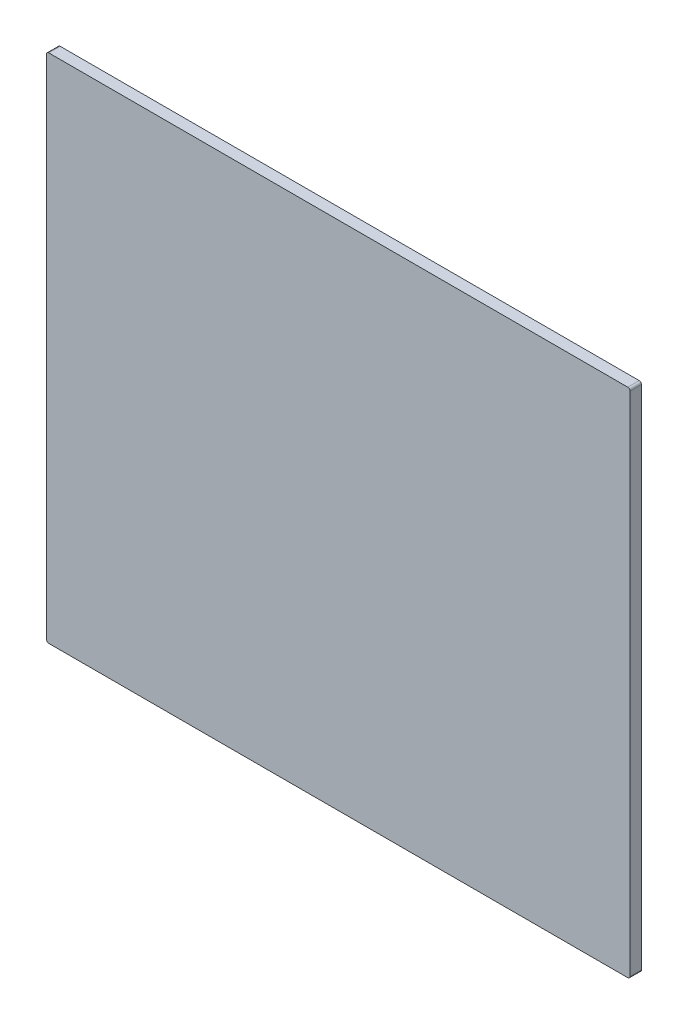
SolidWorks part; units mm, degrees
ref_plane "Front Plane" through (0, 0, 0) normal (0, 0, 1) x (1, 0, 0)
ref_plane "Top Plane" through (0, 0, 0) normal (0, 1, 0) x (1, 0, 0)
ref_plane "Right Plane" through (0, 0, 0) normal (1, 0, 0) x (0, 0, -1)
sketch "Sketch1" plane through (0, 0, 0) normal (0, 0, 1) x (1, 0, 0)
  line L1 (-224.9767, 260.7264) -> (422.7233, 260.7264)
  line L2 (-224.9767, 260.7264) -> (-224.9767, -306.9636)
  line L3 (-224.9767, -306.9636) -> (422.7233, -306.9636)
  line L4 (422.7233, 260.7264) -> (422.7233, -306.9636)
  dimension "D1" = 567.69
  dimension "D2" = 647.7
extrude "Boss-Extrude1" add sketch "Sketch1" along normal blind 12.7 contours L2 L3 L4 L1
fillet "Fillet1" radius 2.54 4 edges at (-224.9767, -306.9636, 6.35) (422.7233, -306.9636, 6.35) (422.7233, 260.7264, 6.35) (-224.9767, 260.7264, 6.35)
